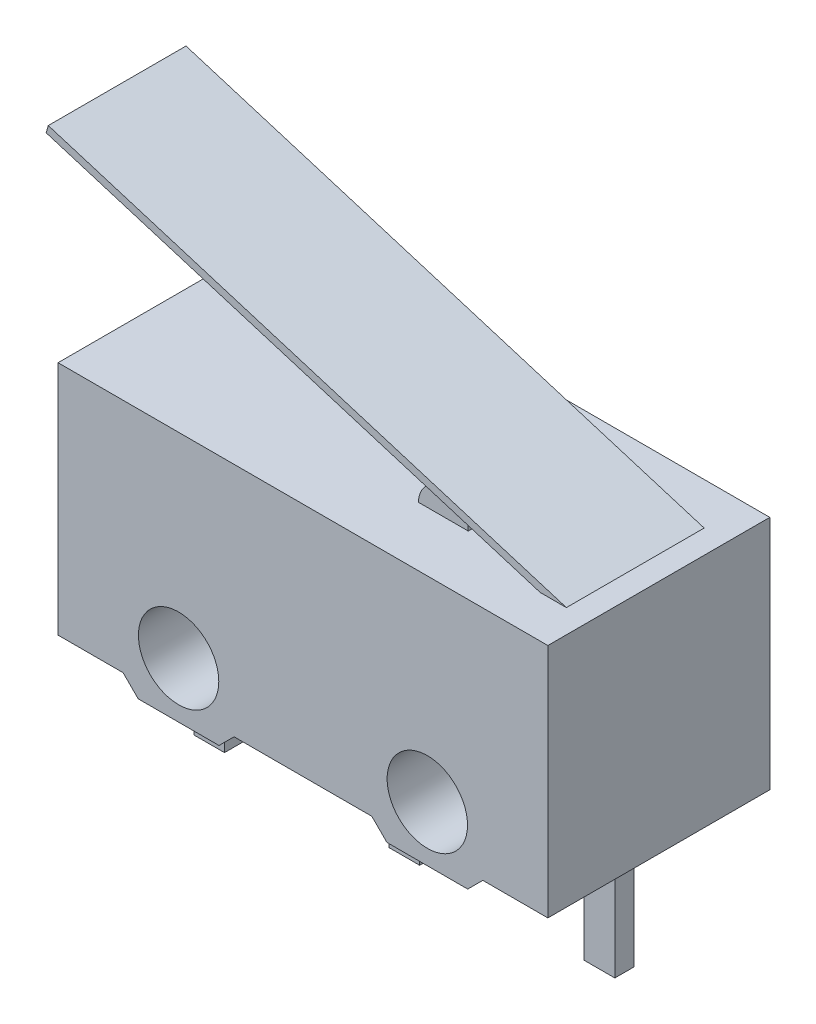
SolidWorks part; units mm, degrees
ref_plane "前视基准面" through (0, 0, 0) normal (0, 0, 1) x (1, 0, 0)
ref_plane "上视基准面" through (0, 0, 0) normal (0, 1, 0) x (1, 0, 0)
ref_plane "右视基准面" through (0, 0, 0) normal (1, 0, 0) x (0, 0, -1)
other "Configuration Table"
sketch "草图1" plane through (0, 0, 0) normal (0, 0, 1) x (1, 0, 0)
  line L0 (0, 0) -> (0, 6.5214) construction
  line L1 (1.8, 0) -> (-1.8, 0)
  line L2 (-1.8, 0) -> (-2.1943, -0.3943)
  line L3 (-2.1943, -0.3943) -> (-4.3057, -0.3943)
  line L4 (-4.3057, -0.3943) -> (-4.7, 0)
  line L5 (-4.7, 0) -> (-6.4, 0)
  line L6 (-6.4, 0) -> (-6.4, 6.1657)
  line L7 (-6.4, 6.1657) -> (6.4, 6.1657)
  line L8 (-3.25, -0.3943) -> (-3.25, 1.05) construction
  line L9 (-4.7, 0) -> (-4.7, -3.1343)
  line L10 (-4.7, -3.1343) -> (-5.5, -3.1343)
  line L11 (-5.5, -3.1343) -> (-5.5, 0)
  line L12 (-5.1, -3.1343) -> (-5.1, -1.5018) construction
  line L13 (-0.4, 0) -> (-0.4, -3.1343)
  line L14 (-0.4, -3.1343) -> (0.4, -3.1343)
  line L15 (5.1, -3.1343) -> (5.1, -1.5018) construction
  line L16 (3.25, -0.3943) -> (3.25, 1.05) construction
  line L17 (0.4, 0) -> (0.4, -3.1343)
  line L18 (5.5, -3.1343) -> (5.5, 0)
  line L19 (4.7, -3.1343) -> (5.5, -3.1343)
  line L20 (4.7, 0) -> (4.7, -3.1343)
  line L21 (6.4, 0) -> (6.4, 6.1657)
  line L22 (4.7, 0) -> (6.4, 0)
  line L23 (4.3057, -0.3943) -> (4.7, 0)
  line L24 (2.1943, -0.3943) -> (4.3057, -0.3943)
  line L25 (1.8, 0) -> (2.1943, -0.3943)
  line L26 (5.1, 6.1657) -> (-7.8101, 10.1127)
  line L27 (-7.8101, 10.1127) -> (-7.7558, 10.3053)
  line L28 (-7.7558, 10.3053) -> (5.7841, 6.1657)
  circle A0 centre (-3.25, 1.05) radius 1.05
  circle A1 centre (3.25, 1.05) radius 1.05
  arc A2 (2.77, 6.1657) -> (1.47, 6.1657) centre (2.12, 6.1657) ccw
  point P28 (0, -3.1343)
  point P34 (0, 6.1657)
  dimension "D2" = 2.1
  dimension "D11" = 1.3
  dimension "D1" = 6.56
  dimension "D3" = 6.5
  dimension "D4" = 135
  dimension "D5" = 12.8
  dimension "D6" = 0.8
  dimension "D7" = 5.1
  dimension "D8" = 9.3
  dimension "D9" = 0.8
  dimension "D10" = 4.28
  dimension "D12" = 17
  dimension "D13" = 13.5
  dimension "D14" = 0.2
extrude "凸台-拉伸1" add sketch "草图1" along normal mid plane 5.8 contours L1 L25 L24 L23 L22 L21 L7 L6 L5 L4 L3 L2 A0 A1
sketch "草图2" plane through (0, 0, 0) normal (0, 0, 1) x (1, 0, 0)
  line L0 (1.47, 6.1657) -> (2.77, 6.1657)
  arc A0 (2.77, 6.1657) -> (1.47, 6.1657) centre (2.12, 6.1657) ccw construction
  arc A1 (2.77, 6.1657) -> (1.47, 6.1657) centre (2.12, 6.1657) ccw
extrude "凸台-拉伸2" add sketch "草图2" along normal mid plane 2.7
sketch "草图3" plane through (0, 0, 0) normal (0, 0, 1) x (1, 0, 0)
  line L0 (4.7, -3.1343) -> (5.5, -3.1343) construction
  line L1 (5.5, -3.1343) -> (5.5, 0) construction
  line L2 (4.7, 0) -> (4.7, -3.1343) construction
  line L3 (0.4, 0) -> (0.4, -3.1343) construction
  line L4 (-0.4, 0) -> (-0.4, -3.1343) construction
  line L5 (-0.4, -3.1343) -> (0.4, -3.1343) construction
  line L6 (-4.7, -3.1343) -> (-5.5, -3.1343) construction
  line L7 (-4.7, 0) -> (-4.7, -3.1343) construction
  line L8 (-5.5, -3.1343) -> (-5.5, 0) construction
  line L9 (4.7, -3.1343) -> (5.5, -3.1343)
  line L10 (5.5, -3.1343) -> (5.5, 0)
  line L11 (4.7, 0) -> (4.7, -3.1343)
  line L12 (0.4, 0) -> (0.4, -3.1343)
  line L13 (-0.4, 0) -> (-0.4, -3.1343)
  line L14 (-0.4, -3.1343) -> (0.4, -3.1343)
  line L15 (-4.7, -3.1343) -> (-5.5, -3.1343)
  line L16 (-4.7, 0) -> (-4.7, -3.1343)
  line L17 (-5.5, -3.1343) -> (-5.5, 0)
  line L18 (-5.5, 0) -> (-4.7, 0)
  line L19 (-0.4, 0) -> (0.4, 0)
  line L20 (4.7, 0) -> (5.5, 0)
extrude "凸台-拉伸3" add sketch "草图3" along normal mid plane 0.5
sketch "草图4" plane through (0, 0, 0) normal (0, 0, 1) x (1, 0, 0)
  line L0 (-7.7558, 10.3053) -> (5.7841, 6.1657) construction
  line L1 (-7.8101, 10.1127) -> (-7.7558, 10.3053) construction
  line L2 (5.1, 6.1657) -> (-7.8101, 10.1127) construction
  line L3 (-7.7558, 10.3053) -> (5.7841, 6.1657)
  line L4 (-7.8101, 10.1127) -> (-7.7558, 10.3053)
  line L5 (5.1, 6.1657) -> (-7.8101, 10.1127)
  line L6 (5.1, 6.1657) -> (5.7841, 6.1657)
extrude "凸台-拉伸4" add sketch "草图4" along normal mid plane 3.6 contours L6 L3 L4 L5
